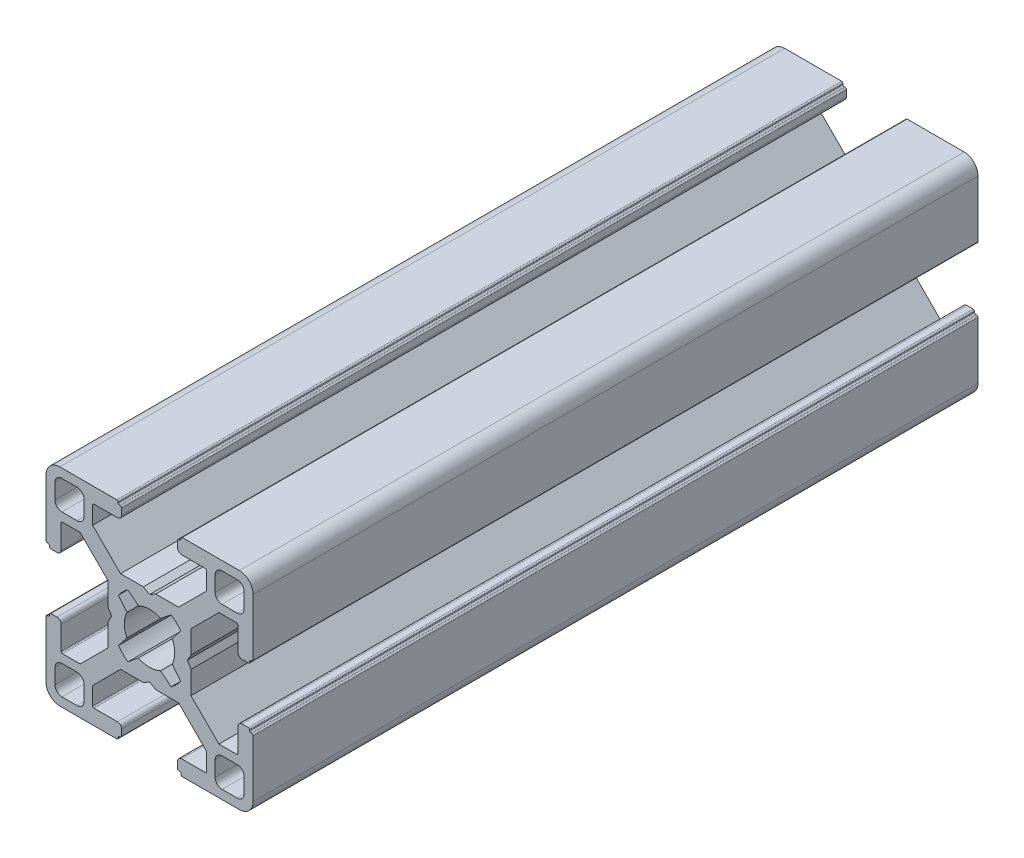
SolidWorks part; units mm, degrees
ref_plane "Front" through (0, 0, 0) normal (0, 0, 1) x (1, 0, 0)
ref_plane "Top" through (0, 0, 0) normal (0, 1, 0) x (1, 0, 0)
ref_plane "Right" through (0, 0, 0) normal (1, 0, 0) x (0, 0, -1)
sketch "Sketch1" plane through (0, 0, 0) normal (0, 0, 1) x (1, 0, 0)
  line L0 (13.7, 12.7) -> (13.7, 10.5)
  line L1 (10.5, 9.5) -> (12.7, 9.5)
  line L2 (9.5, 12.7) -> (9.5, 10.5)
  line L3 (10.5, 13.7) -> (12.7, 13.7)
  line L4 (3.1359, 4.5184) -> (1.6001, 3.2806)
  line L5 (3.2806, 1.6001) -> (4.5053, 3.1547)
  line L6 (6.0045, 0.9) -> (5.4849, 0)
  line L7 (6.0045, 4.2045) -> (6.0045, 0.9)
  line L8 (0, -5.4849) -> (0.9, -6)
  line L9 (0.9, -6) -> (4.2045, -6)
  line L10 (4.2045, -6) -> (8.25, -10.05)
  line L11 (8.25, -10.05) -> (8.25, -12.6)
  line L12 (4.65, -12.8) -> (8.05, -12.8)
  line L13 (4.05, -14.3) -> (4.05, -13.4)
  line L14 (4.25, -14.5) -> (4.35, -14.5)
  line L15 (4.55, -14.8) -> (4.55, -14.7)
  line L16 (4.75, -15) -> (13, -15)
  line L17 (15, -13) -> (15, -4.75)
  line L18 (14.7, -4.55) -> (14.8, -4.55)
  line L19 (14.5, -4.35) -> (14.5, -4.25)
  line L20 (13.4, -4.05) -> (14.3, -4.05)
  line L21 (12.8, -8.05) -> (12.8, -4.65)
  line L22 (12.6, -8.25) -> (10.05, -8.25)
  line L23 (10.05, -8.25) -> (6.0045, -4.2045)
  line L24 (6.0045, -4.2045) -> (6.0045, -0.9)
  line L25 (6.0045, -0.9) -> (5.4849, 0)
  line L26 (10.05, 8.25) -> (6.0045, 4.2045)
  line L27 (12.6, 8.25) -> (10.05, 8.25)
  line L28 (12.8, 8.05) -> (12.8, 4.65)
  line L29 (13.4, 4.05) -> (14.3, 4.05)
  line L30 (14.5, 4.35) -> (14.5, 4.25)
  line L31 (14.7, 4.55) -> (14.8, 4.55)
  line L32 (15, 13) -> (15, 4.75)
  line L33 (4.75, 15) -> (13, 15)
  line L34 (4.55, 14.8) -> (4.55, 14.7)
  line L35 (4.25, 14.5) -> (4.35, 14.5)
  line L36 (4.05, 14.3) -> (4.05, 13.4)
  line L37 (4.65, 12.8) -> (8.05, 12.8)
  line L38 (8.25, 10.05) -> (8.25, 12.6)
  line L39 (4.2045, 6) -> (8.25, 10.05)
  line L40 (0.9, 6) -> (4.2045, 6)
  line L41 (0, 5.4849) -> (0.9, 6)
  line L42 (-13.7, -12.7) -> (-13.7, -10.5)
  line L43 (-10.5, -9.5) -> (-12.7, -9.5)
  line L44 (-9.5, -12.7) -> (-9.5, -10.5)
  line L45 (-10.5, -13.7) -> (-12.7, -13.7)
  line L46 (-3.1359, -4.5184) -> (-1.6001, -3.2806)
  line L47 (-3.2806, -1.6001) -> (-4.5053, -3.1547)
  line L48 (0, 5.4849) -> (-0.9, 6)
  line L49 (-0.9, 6) -> (-4.2045, 6)
  line L50 (-4.2045, 6) -> (-8.25, 10.05)
  line L51 (-8.25, 10.05) -> (-8.25, 12.6)
  line L52 (-4.65, 12.8) -> (-8.05, 12.8)
  line L53 (-4.05, 14.3) -> (-4.05, 13.4)
  line L54 (-4.25, 14.5) -> (-4.35, 14.5)
  line L55 (-4.55, 14.8) -> (-4.55, 14.7)
  line L56 (-4.75, 15) -> (-13, 15)
  line L57 (-15, 13) -> (-15, 4.75)
  line L58 (-14.7, 4.55) -> (-14.8, 4.55)
  line L59 (-14.5, 4.35) -> (-14.5, 4.25)
  line L60 (-13.4, 4.05) -> (-14.3, 4.05)
  line L61 (-12.8, 8.05) -> (-12.8, 4.65)
  line L62 (-12.6, 8.25) -> (-10.05, 8.25)
  line L63 (-10.05, 8.25) -> (-6.0045, 4.2045)
  line L64 (-6.0045, -0.9) -> (-5.4849, 0)
  line L65 (-6.0045, -4.2045) -> (-6.0045, -0.9)
  line L66 (-10.05, -8.25) -> (-6.0045, -4.2045)
  line L67 (-12.6, -8.25) -> (-10.05, -8.25)
  line L68 (-12.8, -8.05) -> (-12.8, -4.65)
  line L69 (-13.4, -4.05) -> (-14.3, -4.05)
  line L70 (-14.5, -4.35) -> (-14.5, -4.25)
  line L71 (-14.7, -4.55) -> (-14.8, -4.55)
  line L72 (-15, -13) -> (-15, -4.75)
  line L73 (-4.75, -15) -> (-13, -15)
  line L74 (-4.55, -14.8) -> (-4.55, -14.7)
  line L75 (-4.25, -14.5) -> (-4.35, -14.5)
  line L76 (-4.05, -14.3) -> (-4.05, -13.4)
  line L77 (3.2806, -1.6001) -> (4.5053, -3.1547)
  line L78 (3.1359, -4.5184) -> (1.6001, -3.2806)
  line L79 (-4.65, -12.8) -> (-8.05, -12.8)
  line L80 (-8.25, -10.05) -> (-8.25, -12.6)
  line L81 (-4.2045, -6) -> (-8.25, -10.05)
  line L82 (-0.9, -6) -> (-4.2045, -6)
  line L83 (0, -5.4849) -> (-0.9, -6)
  line L84 (10.5, -13.7) -> (12.7, -13.7)
  line L85 (9.5, -12.7) -> (9.5, -10.5)
  line L86 (10.5, -9.5) -> (12.7, -9.5)
  line L87 (13.7, -12.7) -> (13.7, -10.5)
  line L88 (-6.0045, 4.2045) -> (-6.0045, 0.9)
  line L89 (-6.0045, 0.9) -> (-5.4849, 0)
  line L90 (-3.2806, 1.6001) -> (-4.5053, 3.1547)
  line L91 (-3.1359, 4.5184) -> (-1.6001, 3.2806)
  line L92 (-10.5, 13.7) -> (-12.7, 13.7)
  line L93 (-9.5, 12.7) -> (-9.5, 10.5)
  line L94 (-10.5, 9.5) -> (-12.7, 9.5)
  line L95 (-13.7, 12.7) -> (-13.7, 10.5)
  line L96 (-23.4857, 0) -> (20.9308, 0) construction
  line L97 (0, 17.9563) -> (0, -17.361) construction
  arc A0 (13.7, 12.7) -> (12.7, 13.7) centre (12.7, 12.7) ccw
  arc A1 (12.7, 9.5) -> (13.7, 10.5) centre (12.7, 10.5) ccw
  arc A2 (9.5, 10.5) -> (10.5, 9.5) centre (10.5, 10.5) ccw
  arc A3 (10.5, 13.7) -> (9.5, 12.7) centre (10.5, 12.7) ccw
  arc A4 (1.6001, 3.2806) -> (-1.6001, 3.2806) centre (0, 0) ccw
  arc A5 (8.25, -12.6) -> (8.05, -12.8) centre (8.05, -12.6) cw
  arc A6 (4.65, -12.8) -> (4.05, -13.4) centre (4.65, -13.4) ccw
  arc A7 (4.05, -14.3) -> (4.25, -14.5) centre (4.25, -14.3) ccw
  arc A8 (4.35, -14.5) -> (4.55, -14.7) centre (4.35, -14.7) cw
  arc A9 (4.55, -14.8) -> (4.75, -15) centre (4.75, -14.8) ccw
  arc A10 (13, -15) -> (15, -13) centre (13, -13) ccw
  arc A11 (15, -4.75) -> (14.8, -4.55) centre (14.8, -4.75) ccw
  arc A12 (14.7, -4.55) -> (14.5, -4.35) centre (14.7, -4.35) cw
  arc A13 (14.5, -4.25) -> (14.3, -4.05) centre (14.3, -4.25) ccw
  arc A14 (13.4, -4.05) -> (12.8, -4.65) centre (13.4, -4.65) ccw
  arc A15 (12.8, -8.05) -> (12.6, -8.25) centre (12.6, -8.05) cw
  arc A16 (4.5053, 3.1547) -> (3.1359, 4.5184) centre (0, 0) ccw
  arc A17 (12.8, 8.05) -> (12.6, 8.25) centre (12.6, 8.05) ccw
  arc A18 (13.4, 4.05) -> (12.8, 4.65) centre (13.4, 4.65) cw
  arc A19 (14.5, 4.25) -> (14.3, 4.05) centre (14.3, 4.25) cw
  arc A20 (14.7, 4.55) -> (14.5, 4.35) centre (14.7, 4.35) ccw
  arc A21 (15, 4.75) -> (14.8, 4.55) centre (14.8, 4.75) cw
  arc A22 (13, 15) -> (15, 13) centre (13, 13) cw
  arc A23 (4.55, 14.8) -> (4.75, 15) centre (4.75, 14.8) cw
  arc A24 (4.35, 14.5) -> (4.55, 14.7) centre (4.35, 14.7) ccw
  arc A25 (4.05, 14.3) -> (4.25, 14.5) centre (4.25, 14.3) cw
  arc A26 (4.65, 12.8) -> (4.05, 13.4) centre (4.65, 13.4) cw
  arc A27 (8.25, 12.6) -> (8.05, 12.8) centre (8.05, 12.6) ccw
  arc A28 (-13.7, -12.7) -> (-12.7, -13.7) centre (-12.7, -12.7) ccw
  arc A29 (-12.7, -9.5) -> (-13.7, -10.5) centre (-12.7, -10.5) ccw
  arc A30 (-9.5, -10.5) -> (-10.5, -9.5) centre (-10.5, -10.5) ccw
  arc A31 (-10.5, -13.7) -> (-9.5, -12.7) centre (-10.5, -12.7) ccw
  arc A32 (-4.5053, -3.1547) -> (-3.1359, -4.5184) centre (0, 0) ccw
  arc A33 (-3.2806, 1.6001) -> (-3.2806, -1.6001) centre (0, 0) ccw
  arc A34 (-8.25, 12.6) -> (-8.05, 12.8) centre (-8.05, 12.6) cw
  arc A35 (-4.65, 12.8) -> (-4.05, 13.4) centre (-4.65, 13.4) ccw
  arc A36 (-4.05, 14.3) -> (-4.25, 14.5) centre (-4.25, 14.3) ccw
  arc A37 (-4.35, 14.5) -> (-4.55, 14.7) centre (-4.35, 14.7) cw
  arc A38 (-4.55, 14.8) -> (-4.75, 15) centre (-4.75, 14.8) ccw
  arc A39 (-13, 15) -> (-15, 13) centre (-13, 13) ccw
  arc A40 (-15, 4.75) -> (-14.8, 4.55) centre (-14.8, 4.75) ccw
  arc A41 (-14.7, 4.55) -> (-14.5, 4.35) centre (-14.7, 4.35) cw
  arc A42 (-14.5, 4.25) -> (-14.3, 4.05) centre (-14.3, 4.25) ccw
  arc A43 (-13.4, 4.05) -> (-12.8, 4.65) centre (-13.4, 4.65) ccw
  arc A44 (-12.8, 8.05) -> (-12.6, 8.25) centre (-12.6, 8.05) cw
  arc A45 (-4.5053, 3.1547) -> (-3.1359, 4.5184) centre (0, 0) cw
  arc A46 (-12.8, -8.05) -> (-12.6, -8.25) centre (-12.6, -8.05) ccw
  arc A47 (-13.4, -4.05) -> (-12.8, -4.65) centre (-13.4, -4.65) cw
  arc A48 (-14.5, -4.25) -> (-14.3, -4.05) centre (-14.3, -4.25) cw
  arc A49 (3.2806, 1.6001) -> (3.2806, -1.6001) centre (0, 0) cw
  arc A50 (4.5053, -3.1547) -> (3.1359, -4.5184) centre (0, 0) cw
  arc A51 (1.6001, -3.2806) -> (-1.6001, -3.2806) centre (0, 0) cw
  arc A52 (-14.7, -4.55) -> (-14.5, -4.35) centre (-14.7, -4.35) ccw
  arc A53 (-15, -4.75) -> (-14.8, -4.55) centre (-14.8, -4.75) cw
  arc A54 (-13, -15) -> (-15, -13) centre (-13, -13) cw
  arc A55 (-4.55, -14.8) -> (-4.75, -15) centre (-4.75, -14.8) cw
  arc A56 (10.5, -13.7) -> (9.5, -12.7) centre (10.5, -12.7) cw
  arc A57 (9.5, -10.5) -> (10.5, -9.5) centre (10.5, -10.5) cw
  arc A58 (12.7, -9.5) -> (13.7, -10.5) centre (12.7, -10.5) cw
  arc A59 (13.7, -12.7) -> (12.7, -13.7) centre (12.7, -12.7) cw
  arc A60 (-4.35, -14.5) -> (-4.55, -14.7) centre (-4.35, -14.7) ccw
  arc A61 (-4.05, -14.3) -> (-4.25, -14.5) centre (-4.25, -14.3) cw
  arc A62 (-4.65, -12.8) -> (-4.05, -13.4) centre (-4.65, -13.4) cw
  arc A63 (-8.25, -12.6) -> (-8.05, -12.8) centre (-8.05, -12.6) ccw
  arc A64 (-10.5, 13.7) -> (-9.5, 12.7) centre (-10.5, 12.7) cw
  arc A65 (-9.5, 10.5) -> (-10.5, 9.5) centre (-10.5, 10.5) cw
  arc A66 (-12.7, 9.5) -> (-13.7, 10.5) centre (-12.7, 10.5) cw
  arc A67 (-13.7, 12.7) -> (-12.7, 13.7) centre (-12.7, 12.7) cw
  point P81 (15, 15)
  point P82 (0, 15)
  point P203 (0, -15)
  point P204 (15, -15)
  point P206 (0, 0)
  point P207 (15, 0)
  point P219 (-15, 0)
  point P220 (-15, -15)
  point P221 (-15, 15)
  dimension "D6" = 7.3
  dimension "D7" = 11
  dimension "D1" = 30
  dimension "D2" = 15
  dimension "D3" = 30
  dimension "D4" = 8.1
  dimension "D5" = 9
  dimension "D8" = 8.1
extrude "Base-Extrude" add sketch "Sketch1" against normal blind 105
